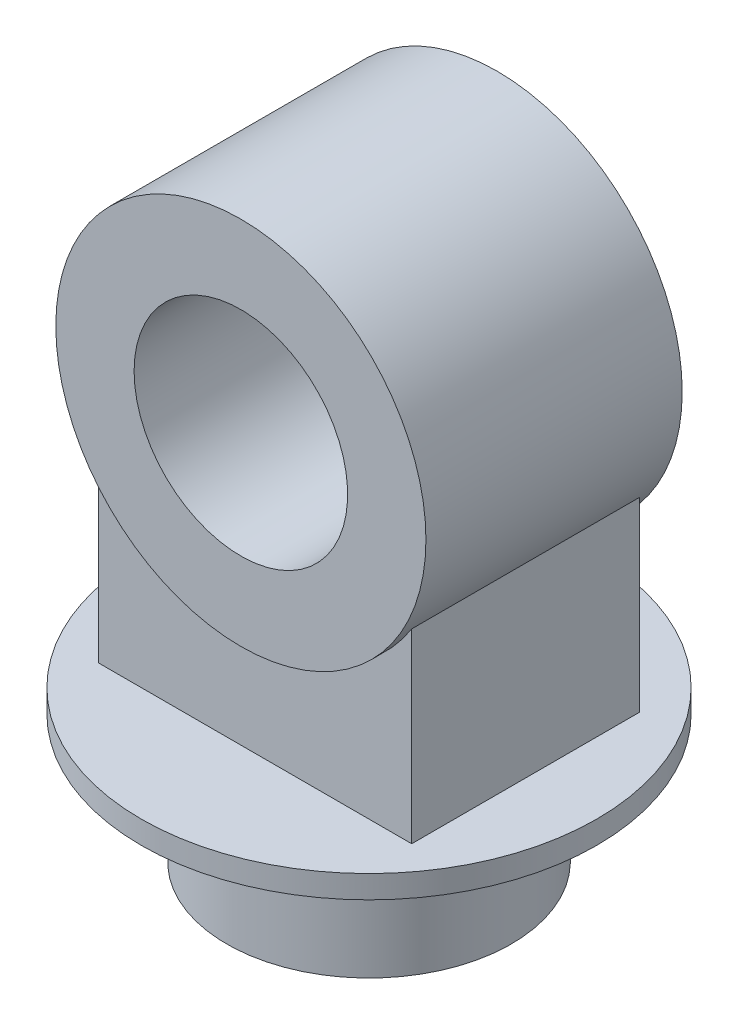
SolidWorks part; units mm, degrees
material "Cast Carbon Steel"
ref_plane "Front Plane" through (0, 0, 0) normal (0, 0, 1) x (1, 0, 0)
ref_plane "Top Plane" through (0, 0, 0) normal (0, 1, 0) x (1, 0, 0)
ref_plane "Right Plane" through (0, 0, 0) normal (1, 0, 0) x (0, 0, -1)
sketch "Sketch1" plane through (0, 0, 0) normal (0, 1, 0) x (1, 0, 0)
  circle A0 centre (0, 0) radius 100
  dimension "D1" = 200
extrude "Boss-Extrude1" add sketch "Sketch1" along normal blind 90
sketch "Sketch2" plane through (0, 90, 0) normal (0, 1, 0) x (1, 0, 0)
  circle A0 centre (0, 0) radius 160
  dimension "D1" = 320
extrude "Boss-Extrude2" add sketch "Sketch2" along normal blind 16
sketch "Sketch3" plane through (0, 0, 0) normal (0, 0, 1) x (1, 0, 0)
  line L0 (160, 106) -> (-160, 106) construction
  circle A0 centre (0, 306) radius 130
  circle A1 centre (0, 306) radius 75
  dimension "D1" = 260
  dimension "D2" = 55
  dimension "D3" = 200
extrude "Boss-Extrude3" add sketch "Sketch3" along normal mid plane 180 separate body
sketch "Sketch4" plane through (0, 106, 0) normal (0, 1, 0) x (1, 0, 0)
  line L1 (-110, 80) -> (110, 80)
  line L2 (-110, 80) -> (-110, -80)
  line L3 (-110, -80) -> (110, -80)
  line L4 (110, 80) -> (110, -80)
  line L5 (-110, 80) -> (110, -80) construction
  line L6 (-110, -80) -> (110, 80) construction
  point P0 (0, 0)
  dimension "D1" = 220
  dimension "D2" = 160
extrude "Boss-Extrude4" add sketch "Sketch4" along normal up to next
